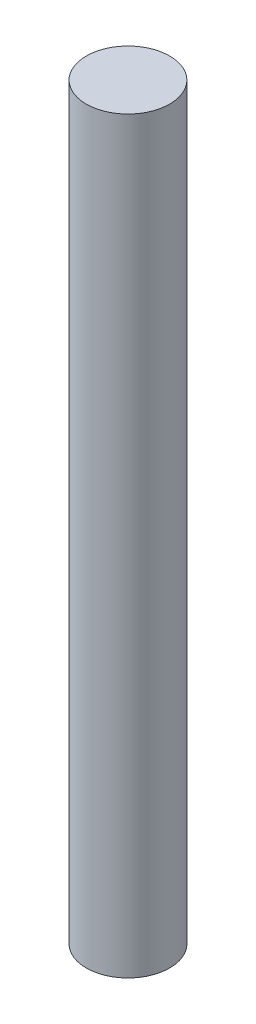
SolidWorks part; units mm, degrees
ref_plane "Front Plane" through (0, 0, 0) normal (0, 0, 1) x (1, 0, 0)
ref_plane "Top Plane" through (0, 0, 0) normal (0, 1, 0) x (1, 0, 0)
ref_plane "Right Plane" through (0, 0, 0) normal (1, 0, 0) x (0, 0, -1)
sketch "Sketch1" plane through (0, 0, 0) normal (0, 1, 0) x (1, 0, 0)
  circle A0 centre (0, 0) radius 1.95
  dimension "D1" = 3.9
extrude "Boss-Extrude1" add sketch "Sketch1" along normal blind 35
